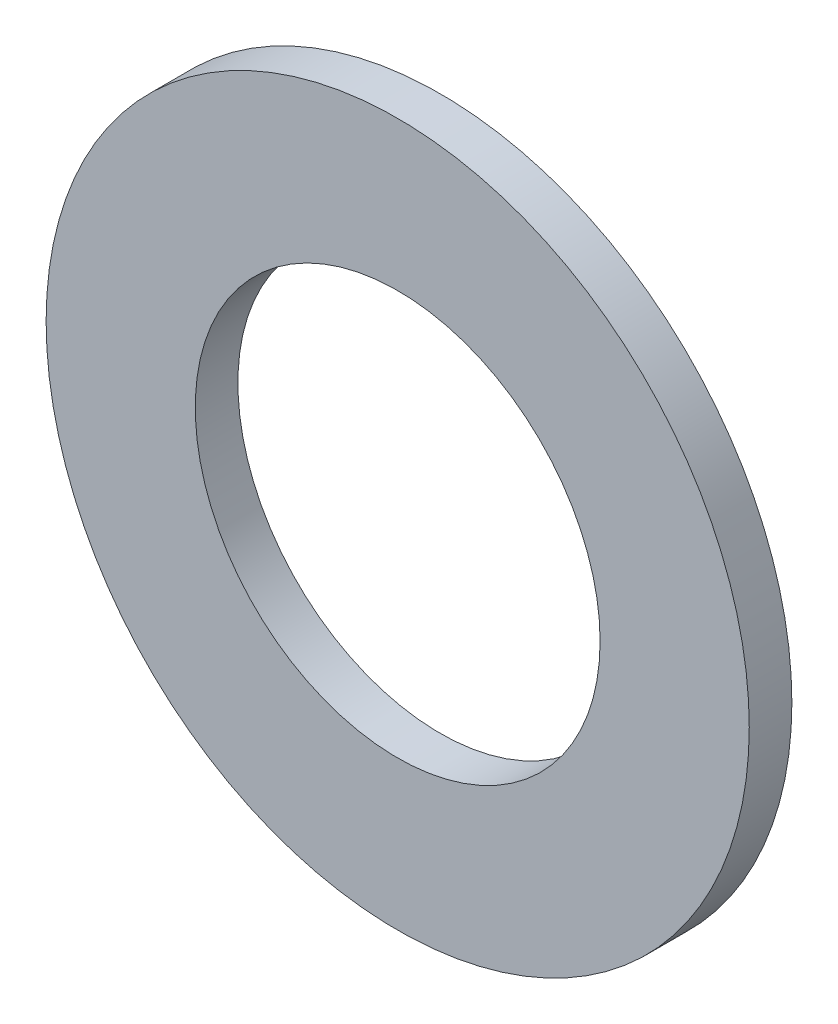
SolidWorks part; units mm, degrees
ref_plane "Front Plane" through (0, 0, 0) normal (0, 0, 1) x (1, 0, 0)
ref_plane "Top Plane" through (0, 0, 0) normal (0, 1, 0) x (1, 0, 0)
ref_plane "Right Plane" through (0, 0, 0) normal (1, 0, 0) x (0, 0, -1)
sketch "Sketch1" plane through (0, 0, 0) normal (0, 0, 1) x (1, 0, 0)
  circle A0 centre (0, 0) radius 9.652
  circle A1 centre (0, 0) radius 16.764
  point P4 (-9.652, 0)
  dimension "ID" = 19.304
  dimension "OD" = 33.528
extrude "Extrude1" add sketch "Sketch1" against normal blind 2.032
